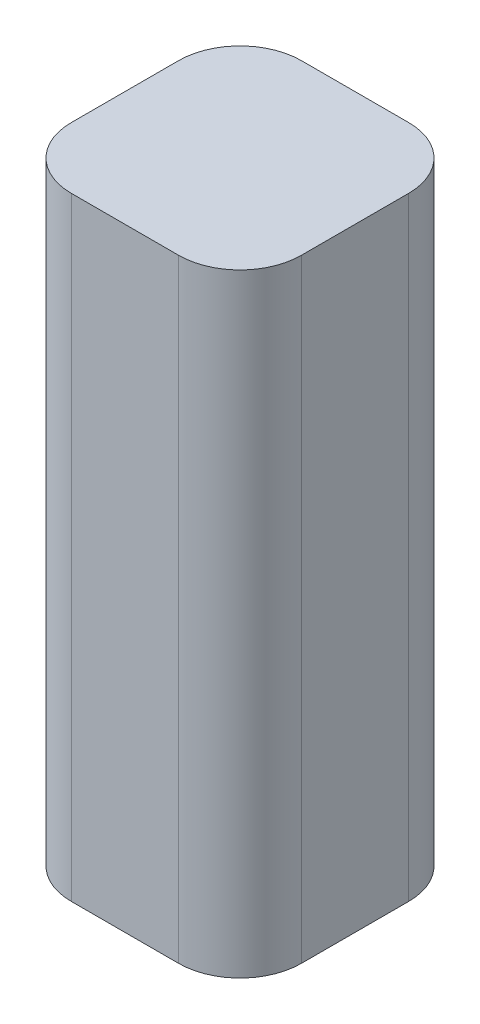
SolidWorks part; units mm, degrees
material "PLA"
ref_plane "Front Plane" through (0, 0, 0) normal (0, 0, 1) x (1, 0, 0)
ref_plane "Top Plane" through (0, 0, 0) normal (0, 1, 0) x (1, 0, 0)
ref_plane "Right Plane" through (0, 0, 0) normal (1, 0, 0) x (0, 0, -1)
sketch "Sketch1" plane through (0, 0, 0) normal (0, 1, 0) x (1, 0, 0)
  line L0 (-3.75, -1.75) -> (-3.75, 1.75)
  line L1 (-1.75, 3.75) -> (1.75, 3.75)
  line L2 (3.75, 1.75) -> (3.75, -1.75)
  line L3 (1.75, -3.75) -> (-1.75, -3.75)
  arc A0 (-3.75, 1.75) -> (-1.75, 3.75) centre (-1.75, 1.75) cw
  arc A1 (1.75, 3.75) -> (3.75, 1.75) centre (1.75, 1.75) cw
  arc A2 (3.75, -1.75) -> (1.75, -3.75) centre (1.75, -1.75) cw
  arc A3 (-1.75, -3.75) -> (-3.75, -1.75) centre (-1.75, -1.75) cw
  point P12 (0, 3.75)
  point P14 (3.75, 0)
  dimension "D3" = 2
  dimension "D1" = 7.5
extrude "Boss-Extrude1" add sketch "Sketch1" along normal mid plane 20
